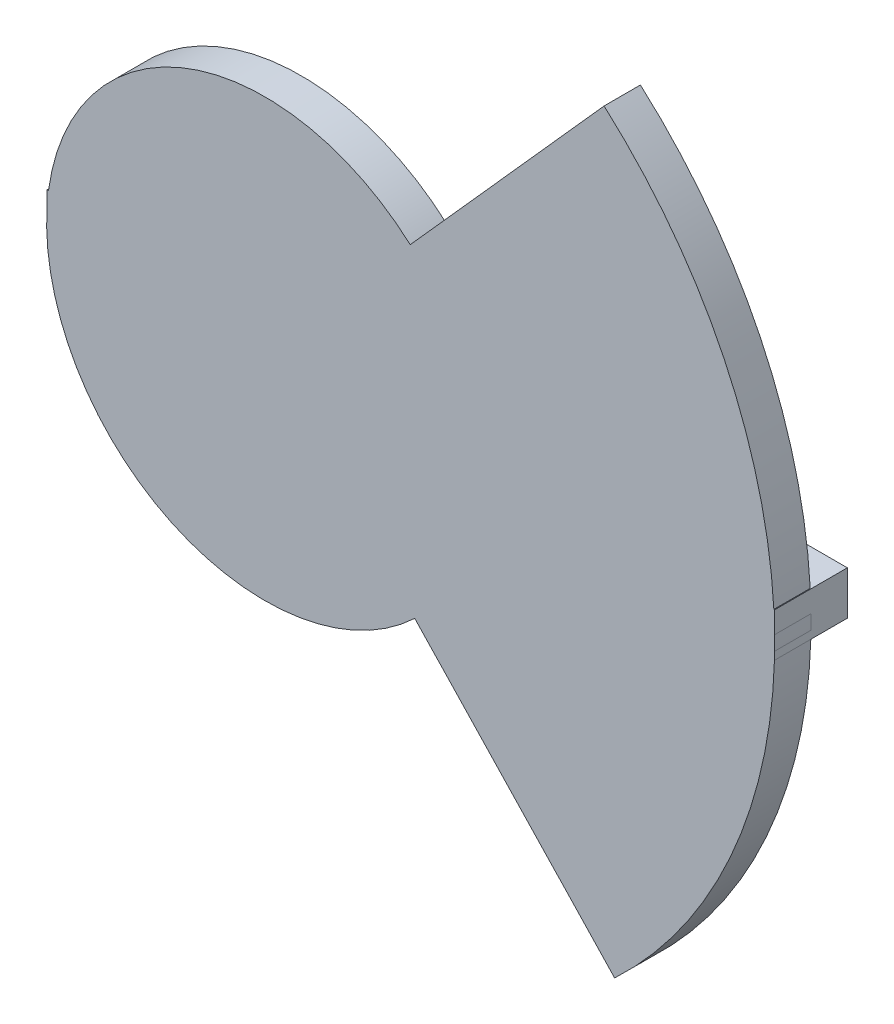
SolidWorks part; units mm, degrees
ref_plane "Front Plane" through (0, 0, 0) normal (0, 0, 1) x (1, 0, 0)
ref_plane "Top Plane" through (0, 0, 0) normal (0, 1, 0) x (1, 0, 0)
ref_plane "Right Plane" through (0, 0, 0) normal (1, 0, 0) x (0, 0, -1)
sketch "Sketch3" plane through (0, 0, 0) normal (0, 0, 1) x (1, 0, 0)
  line L2 (-4.165, 23.8738) -> (19.3918, 59.8282)
  line L3 (49.464, 2.7315) -> (-50.536, 2.7315)
  line L4 (49.464, 2.7315) -> (49.464, -3.2685)
  line L5 (49.464, -3.2685) -> (-50.536, -3.2685)
  line L6 (-50.536, 2.7315) -> (-50.536, -3.2685)
  line L7 (49.464, 2.7315) -> (-50.536, -3.2685) construction
  line L8 (49.464, -3.2685) -> (-50.536, 2.7315) construction
  line L9 (2.7988, -19.9873) -> (34.7967, -45.6453)
  circle A6 centre (-20.606, -1.2199) radius 30
  circle A7 centre (-20.606, -1.2199) radius 20
  arc A8 (19.3918, 59.8282) -> (34.7967, -45.6453) centre (-26.5842, -0.7486) cw
  arc A9 (-4.165, 23.8738) -> (2.7988, -19.9873) centre (-20.606, -1.2199) cw
  point P3 (-0.536, -0.2685)
  dimension "D1" = 60
  dimension "D2" = 40
  dimension "D3" = 6
  dimension "D4" = 100
extrude "Boss-Extrude3" add sketch "Sketch3" against normal blind 10 contours L3 A7
sketch "Sketch5" plane through (0, 0, 0) normal (0, 0, 1) x (1, 0, 0)
  line L0 (-0.6227, 21.1557) -> (26.0217, 50.9898)
  line L1 (0, -23.0234) -> (27.4747, -52.0948)
  line L2 (49.464, 2.7315) -> (49.464, -3.2685) construction
  circle A0 centre (-20.606, -1.2199) radius 30
  arc A1 (26.0217, 50.9898) -> (27.4747, -52.0948) centre (-20.3687, -1.2166) cw
  arc A2 (-0.6227, 21.1557) -> (0, -23.0234) centre (-20.606, -1.2199) cw
  point P9 (49.464, -0.2323)
  point P12 (49.464, -0.2685)
  dimension "D1" = 40
  dimension "D2" = 0
extrude "Boss-Extrude4" add sketch "Sketch5" against normal blind 5 contours A1 L0 A0 L1 | A0
